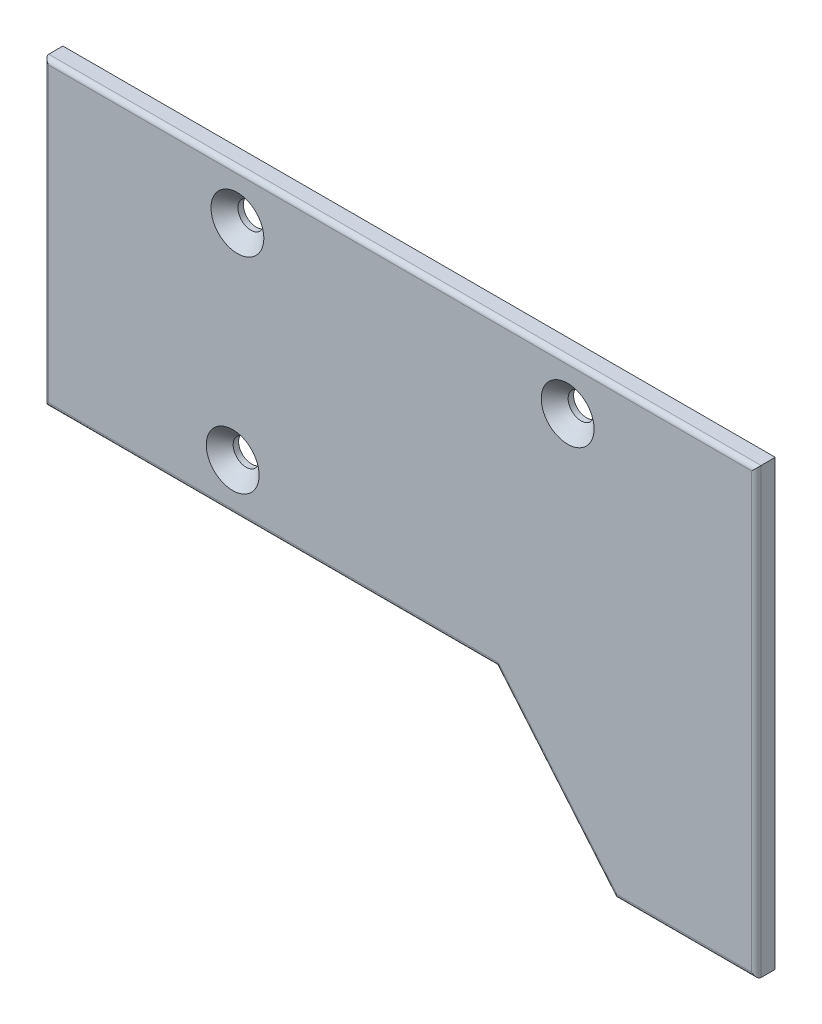
SolidWorks part; units mm, degrees
ref_plane "Front Plane" through (0, 0, 0) normal (0, 0, 1) x (1, 0, 0)
ref_plane "Top Plane" through (0, 0, 0) normal (0, 1, 0) x (1, 0, 0)
ref_plane "Right Plane" through (0, 0, 0) normal (1, 0, 0) x (0, 0, -1)
sketch "Sketch1" plane through (0, 0, 0) normal (0, 0, 1) x (1, 0, 0)
  line L0 (0, 0) -> (0, 64)
  line L1 (0, 64) -> (151, 64)
  line L2 (151, 64) -> (151, -30)
  line L3 (151, -30) -> (121, -30)
  line L4 (121, -30) -> (95.827, 0)
  line L5 (95.827, 0) -> (0, 0)
  circle A0 centre (41, 54) radius 2.75
  circle A1 centre (111, 54) radius 2.75
  circle A2 centre (40, 10) radius 2.75
  dimension "D11" = 5.5
  dimension "D1" = 30
  dimension "D2" = 151
  dimension "D3" = 130
  dimension "D4" = 30
  dimension "D5" = 64
  dimension "D6" = 10
  dimension "D7" = 10
  dimension "D8" = 70
  dimension "D9" = 40
  dimension "D10" = 40
extrude "Boss-Extrude1" add sketch "Sketch1" along normal blind 4
fillet "Fillet1" radius 1 6 edges at (0, 32, 4) (75.5, 64, 4) (151, 17, 4) (136, -30, 4) (108.4135, -15, 4) (47.9135, 0, 4)
hole_wizard "CSK for M5 Hex Socket Countersunk Cap Screw1" positions "Sketch2" profile "Sketch3" countersink size "M5" standard "ISO"
sketch "Sketch2" plane through (0, 0, 4) normal (0, 0, 1) x (1, 0, 0)
  point P0 (41, 54)
  point P3 (111, 54)
  point P6 (40, 10)
sketch "Sketch3" plane through (41, 54, 4) normal (1, 0, 0) x (0, -1, 0)
  line L0 (0, 0) -> (0, 14.0524)
  line L1 (0, 14.0524) -> (2.75, 12.4)
  line L2 (2.75, 12.4) -> (2.75, 2.85)
  line L3 (2.75, 2.85) -> (5.6, 0)
  line L5 (5.6, 0) -> (0, 0)
  line L6 (-2.75, 2.85) -> (-5.6, 0) construction
  line L10 (0, 14.0524) -> (-2.75, 12.4) construction
  line L11 (0, -6.35) -> (0, 107.95) construction
  dimension "Hole Dia." = 5.5
  dimension "Hole Depth" = 12.4
  dimension "Near C'Sink Dia." = 11.2
  dimension "Near C'Sink Angle" = 90
  dimension "Drill Angle" = 118
